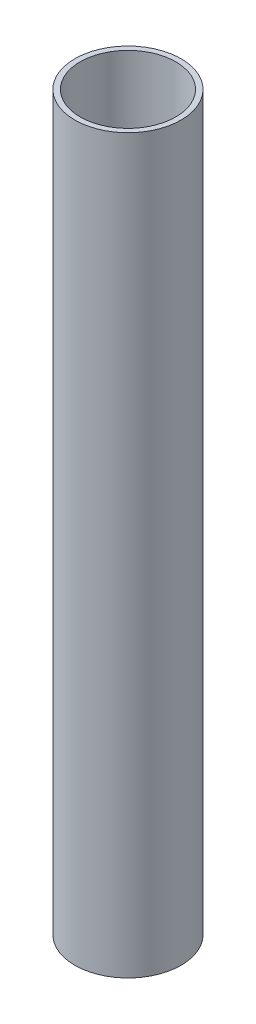
SolidWorks part; units mm, degrees
ref_plane "Front Plane" through (0, 0, 0) normal (0, 0, 1) x (1, 0, 0)
ref_plane "Top Plane" through (0, 0, 0) normal (0, 1, 0) x (1, 0, 0)
ref_plane "Right Plane" through (0, 0, 0) normal (1, 0, 0) x (0, 0, -1)
sketch "Sketch1" plane through (0, 0, 0) normal (0, 1, 0) x (1, 0, 0)
  circle A0 centre (0, 0) radius 10
  circle A1 centre (0, 0) radius 9
extrude "Boss-Extrude1" add sketch "Sketch1" along normal blind 137.8
